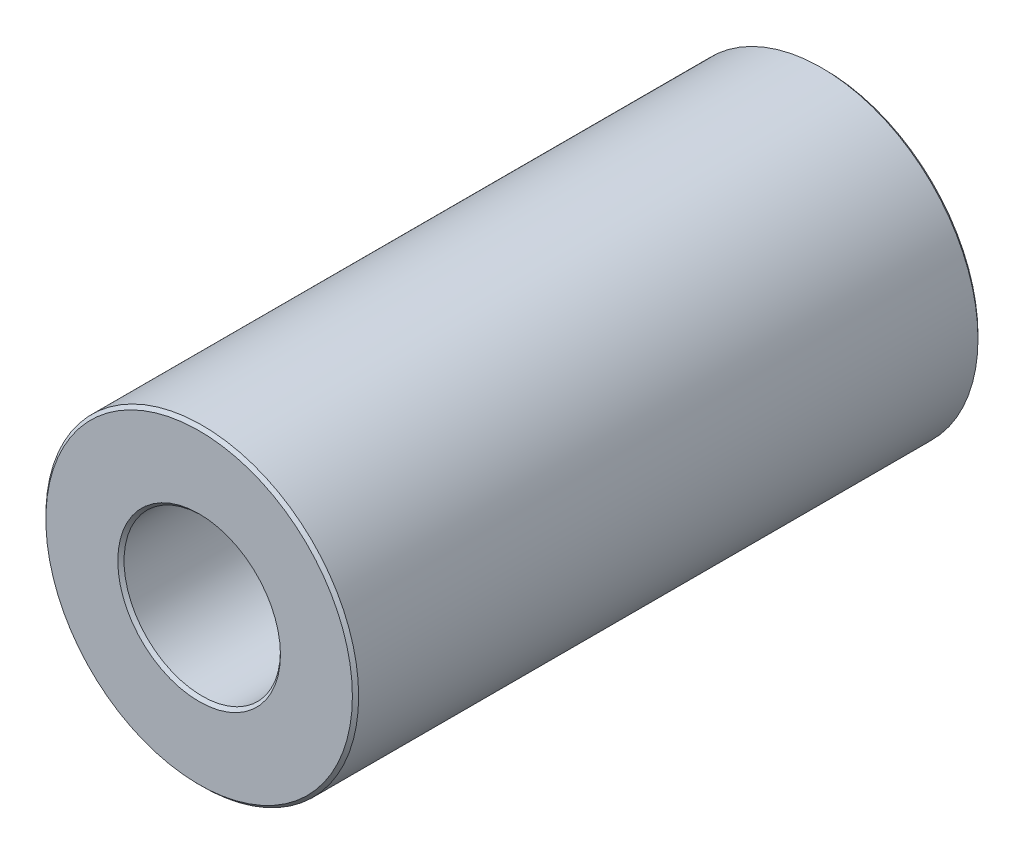
SolidWorks part; units mm, degrees
ref_plane "Front Plane" through (0, 0, 0) normal (0, 0, 1) x (1, 0, 0)
ref_plane "Top Plane" through (0, 0, 0) normal (0, 1, 0) x (1, 0, 0)
ref_plane "Right Plane" through (0, 0, 0) normal (1, 0, 0) x (0, 0, -1)
sketch "Sketch2" plane through (0, 0, 0) normal (0, 0, 1) x (1, 0, 0)
  circle A0 centre (0, 0) radius 12.7
  circle A1 centre (0, 0) radius 6.35
  dimension "D1" = 25.4
  dimension "D2" = 12.7
extrude "Boss-Extrude1" add sketch "Sketch2" along normal mid plane 50.8 contours A0 | A1
chamfer "Chamfer1" distance 0.254 angle 45 4 edges at (12.7, 0, -25.4) (12.7, 0, 25.4) (6.35, 0, -25.4) (6.35, 0, 25.4)
